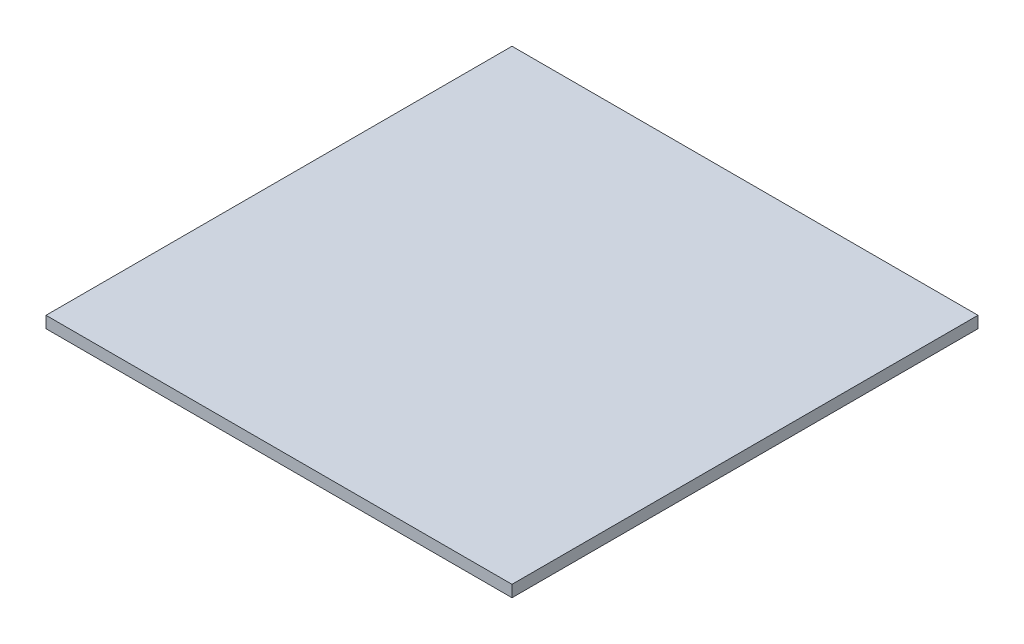
SolidWorks part; units mm, degrees
ref_plane "前视基准面" through (0, 0, 0) normal (0, 0, 1) x (1, 0, 0)
ref_plane "上视基准面" through (0, 0, 0) normal (0, 1, 0) x (1, 0, 0)
ref_plane "右视基准面" through (0, 0, 0) normal (1, 0, 0) x (0, 0, -1)
other "Configuration Table"
sketch "草图2" plane through (0, 0, 0) normal (0, 1, 0) x (1, 0, 0)
  line L1 (-2000, 2000) -> (2000, 2000)
  line L2 (-2000, 2000) -> (-2000, -2000)
  line L3 (-2000, -2000) -> (2000, -2000)
  line L4 (2000, 2000) -> (2000, -2000)
  line L5 (-2000, 2000) -> (2000, -2000) construction
  line L6 (-2000, -2000) -> (2000, 2000) construction
  point P0 (0, 0)
  dimension "D1" = 4000
  dimension "D2" = 4000
extrude "凸台-拉伸1" add sketch "草图2" along normal blind 100
